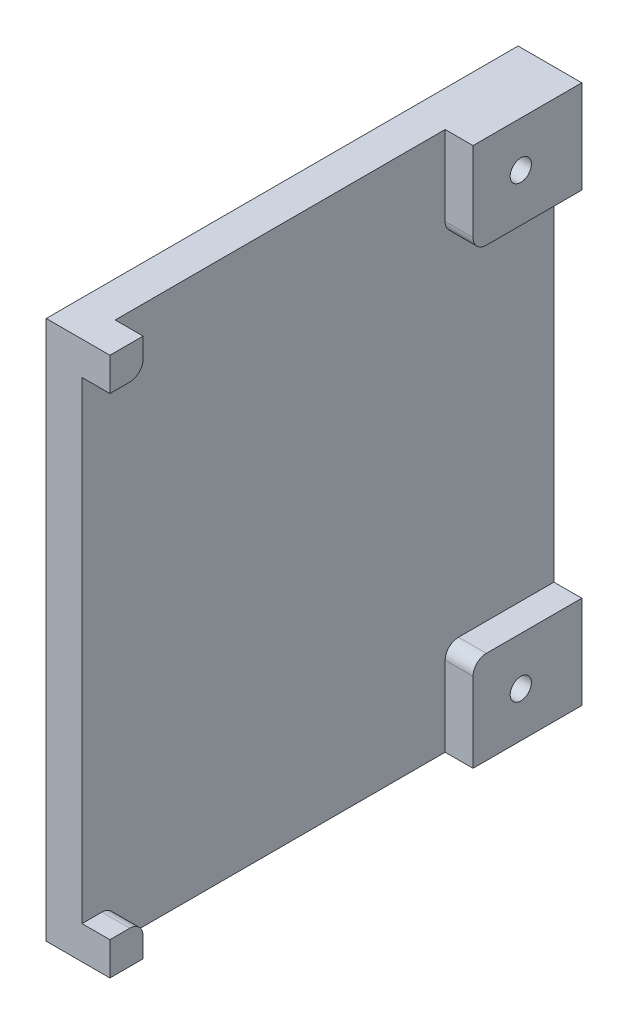
SolidWorks part; units mm, degrees
ref_plane "Front Plane" through (0, 0, 0) normal (1, 0, 0) x (0, 1, 0)
ref_plane "Top Plane" through (0, 0, 0) normal (0, 0, 1) x (0, 1, 0)
ref_plane "Right Plane" through (0, 0, 0) normal (0, 1, 0) x (-1, 0, 0)
sketch "Sketch1" plane through (0, 0, 0) normal (1, 0, 0) x (0, 1, 0)
  line L10 (-20.32, 17.78) -> (20.32, 17.78) construction
  line L11 (-20.32, 17.78) -> (-20.32, -17.78) construction
  line L18 (-20.32, -17.78) -> (20.32, -17.78) construction
  line L19 (20.32, 17.78) -> (20.32, -17.78) construction
  line L20 (-20.32, 17.78) -> (20.32, -17.78) construction
  line L21 (-20.32, -17.78) -> (20.32, 17.78) construction
  line L22 (-20.32, 17.78) -> (20.32, 17.78)
  line L23 (-20.32, 17.78) -> (-20.32, -17.78)
  line L24 (-20.32, -17.78) -> (20.32, -17.78)
  line L25 (20.32, 17.78) -> (20.32, -17.78)
  line L26 (-20.32, 17.78) -> (20.32, -17.78) construction
  line L27 (-20.32, -17.78) -> (20.32, 17.78) construction
  point P0 (0, 0)
  point P5 (0, 0)
  dimension "D1" = 40.64
  dimension "D2" = 35.56
extrude "Boss-Extrude1" add sketch "Sketch1" along normal blind 3 contours L25 L22 L23 L24
sketch "Sketch3" plane through (3, 0, 0) normal (1, 0, 0) x (0, 1, 0)
  line L0 (-20.32, -17.78) -> (20.32, -17.78) construction
  line L1 (-20.32, 17.78) -> (20.32, 17.78) construction
  line L2 (-20.32, 17.78) -> (-20.32, -17.78) construction
  line L3 (-20.32, -17.78) -> (20.32, -17.78) construction
  line L4 (20.32, 17.78) -> (20.32, -17.78) construction
  line L5 (-20.32, 17.78) -> (20.32, -17.78) construction
  line L6 (-20.32, -17.78) -> (20.32, 17.78) construction
  line L7 (0, 0) -> (0, -50000) construction
  line L8 (-20.32, -17.78) -> (-13.3164, -17.78)
  line L9 (-20.32, -17.78) -> (-20.32, -9.5826)
  line L10 (-20.32, -9.5826) -> (-13.3164, -9.5826)
  line L11 (-13.3164, -17.78) -> (-13.3164, -9.5826)
  line L12 (-20.32, 17.78) -> (-17.82, 17.78)
  line L13 (-20.32, 17.78) -> (-20.32, 15.28)
  line L14 (-20.32, 15.28) -> (-17.82, 15.28)
  line L15 (-17.82, 17.78) -> (-17.82, 15.28)
  line L16 (20.32, 17.78) -> (20.32, -17.78) construction
  line L17 (17.82, 17.78) -> (17.82, 15.28)
  line L18 (20.32, 15.28) -> (17.82, 15.28)
  line L19 (20.32, 17.78) -> (20.32, 15.28)
  line L20 (20.32, 17.78) -> (17.82, 17.78)
  line L21 (13.3164, -17.78) -> (13.3164, -9.5826)
  line L22 (20.32, -9.5826) -> (13.3164, -9.5826)
  line L23 (20.32, -17.78) -> (20.32, -9.5826)
  line L24 (20.32, -17.78) -> (13.3164, -17.78)
  circle A0 centre (-16.9164, -13.1826) radius 1.8 construction
  circle A1 centre (16.9164, -13.1826) radius 1.8 construction
  point P0 (0, 0)
  line M17 (20.32, 17.78) -> (-20.32, 17.78)
  line M19 (-20.32, -17.78) -> (20.32, -17.78)
  dimension "D2" = 3.6
  dimension "D5" = 3.6
  dimension "D1" = 40.64
  dimension "D3" = 3.4036
  dimension "D4" = 4.5974
  dimension "D6" = 3.6
  dimension "D7" = 2.5
  dimension "D8" = 2.5
extrude "Boss-Extrude2" add sketch "Sketch3" along normal blind 2.1 contours L11 L10 L9 M19 | L23 L22 L21 M19 | L19 L17 L18 M17 | L15 L13 L14 M17
sketch "Sketch4" plane through (5.1, 0, 0) normal (1, 0, 0) x (0, 1, 0)
  circle A0 centre (-16.9164, -13.1826) radius 0.8
  circle A1 centre (16.9164, -13.1826) radius 0.8
  dimension "D1" = 1.6
extrude "Cut-Extrude2" cut sketch "Sketch4" against normal through all contours A0 | A1
fillet "Fillet1" radius 1 4 edges at (4.05, -13.3164, -9.5826) (4.05, 13.3164, -9.5826) (4.05, 17.82, 15.28) (4.05, -17.82, 15.28)
chamfer "Chamfer1" distance 0.3 angle 45 6 edges at (0, 0, 17.78) (0, -20.32, 0) (0, 0, -17.78) (0, 20.32, 0) (0, 16.9164, -13.9826) (0, -16.9164, -13.9826)
equation "\"PCB_Width\"= 1.05in"
equation "\"PCB_Length\"= 1.35in"
equation "\"PCB_Thickness\"= 1.50404mm"
equation "\"USB_Height\"= 3.36mm"
equation "\"ZIF_Height\"= 2mm"
equation "\"Case_Thickness\"= 5mm"
